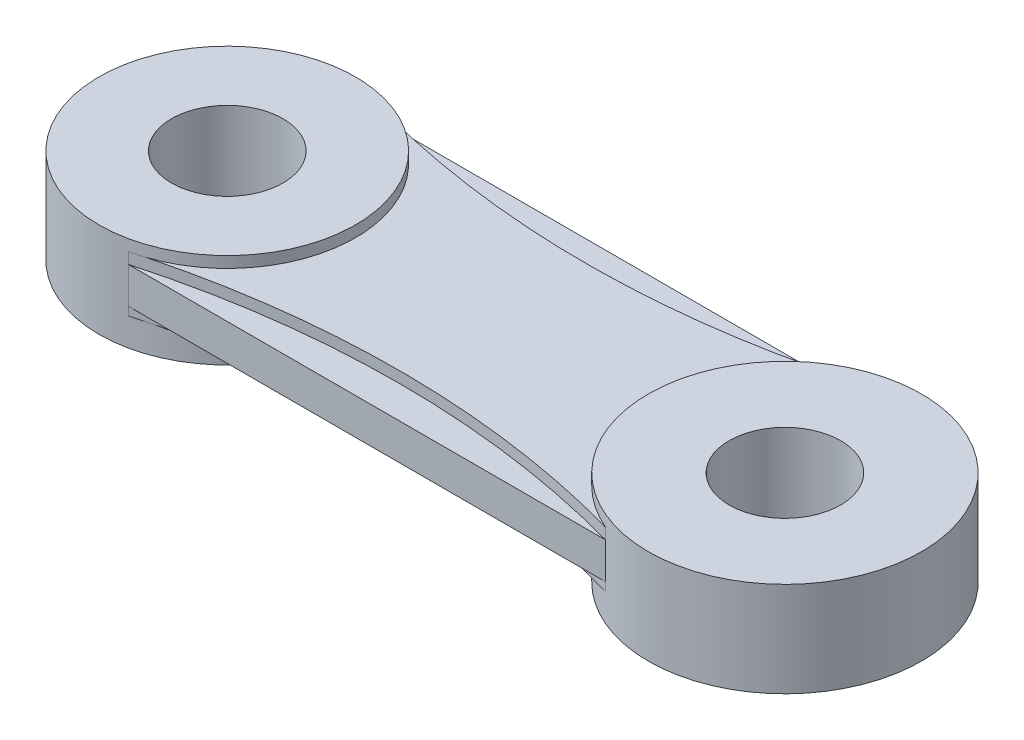
SolidWorks part; units mm, degrees
ref_plane "Alzado" through (0, 0, 0) normal (0, 0, 1) x (1, 0, 0)
ref_plane "Planta" through (0, 0, 0) normal (0, 1, 0) x (1, 0, 0)
ref_plane "Vista lateral" through (0, 0, 0) normal (1, 0, 0) x (0, 0, -1)
sketch "Croquis3" plane through (0, 0, 0) normal (0, 1, 0) x (1, 0, 0)
  line L1 (0, 0) -> (1000, 0)
  line L2 (0, 0) -> (0, 450)
  line L3 (0, 450) -> (1000, 450)
  line L4 (1000, 0) -> (1000, 450)
  dimension "D1" = 1000
  dimension "D2" = 450
extrude "Saliente-Extruir4" add sketch "Croquis3" along normal blind 100
sketch "Croquis6" plane through (0, 100, 0) normal (0, 1, 0) x (1, 0, 0)
  line L0 (1000, 0) -> (1000, 450) construction
  line L1 (0, 450) -> (0, 0) construction
  circle A0 centre (1000, 225) radius 245
  circle A1 centre (0, 225) radius 230
  dimension "D1" = 490
  dimension "D2" = 460
extrude "Saliente-Extruir5" add sketch "Croquis6" along normal blind 20 and the other way blind 150
sketch "Croquis7" plane through (0, 100, 0) normal (0, 1, 0) x (1, 0, 0)
  line L0 (47.697, 0) -> (903.0464, 0)
  line L1 (-230, 225) -> (1245, 225) construction
  line L2 (47.697, 450) -> (903.0464, 450)
  arc A0 (47.697, 0) -> (903.0464, 0) centre (475.3717, -1541.7828) cw
  circle A1 centre (1000, 225) radius 245 construction
  circle A2 centre (0, 225) radius 230 construction
  arc A3 (47.697, 450) -> (903.0464, 450) centre (475.3717, 1991.7828) ccw
  dimension "D1" = 1600
extrude "Cortar-Extruir5" cut sketch "Croquis7" against normal blind 20
sketch "Croquis8" plane through (0, 120, 0) normal (0, 1, 0) x (1, 0, 0)
  circle A0 centre (0, 225) radius 100
  circle A1 centre (1000, 225) radius 100
  dimension "D1" = 200
  dimension "D2" = 200
extrude "Cortar-Extruir4" cut sketch "Croquis8" against normal through all both and the other way through all
sketch "Croquis9" plane through (0, 0, 0) normal (0, -1, 0) x (1, 0, 0)
  line L0 (47.697, 0) -> (903.0464, 0)
  line L1 (-230, -225) -> (1245, -225) construction
  line L2 (47.697, -450) -> (903.0464, -450)
  arc A0 (47.697, 0) -> (903.0464, 0) centre (475.3717, 1541.7828) ccw
  circle A1 centre (0, -225) radius 230 construction
  circle A2 centre (1000, -225) radius 245 construction
  arc A3 (47.697, -450) -> (903.0464, -450) centre (475.3717, -1991.7828) cw
  dimension "D1" = 1600
extrude "Cortar-Extruir6" cut sketch "Croquis9" against normal blind 15
